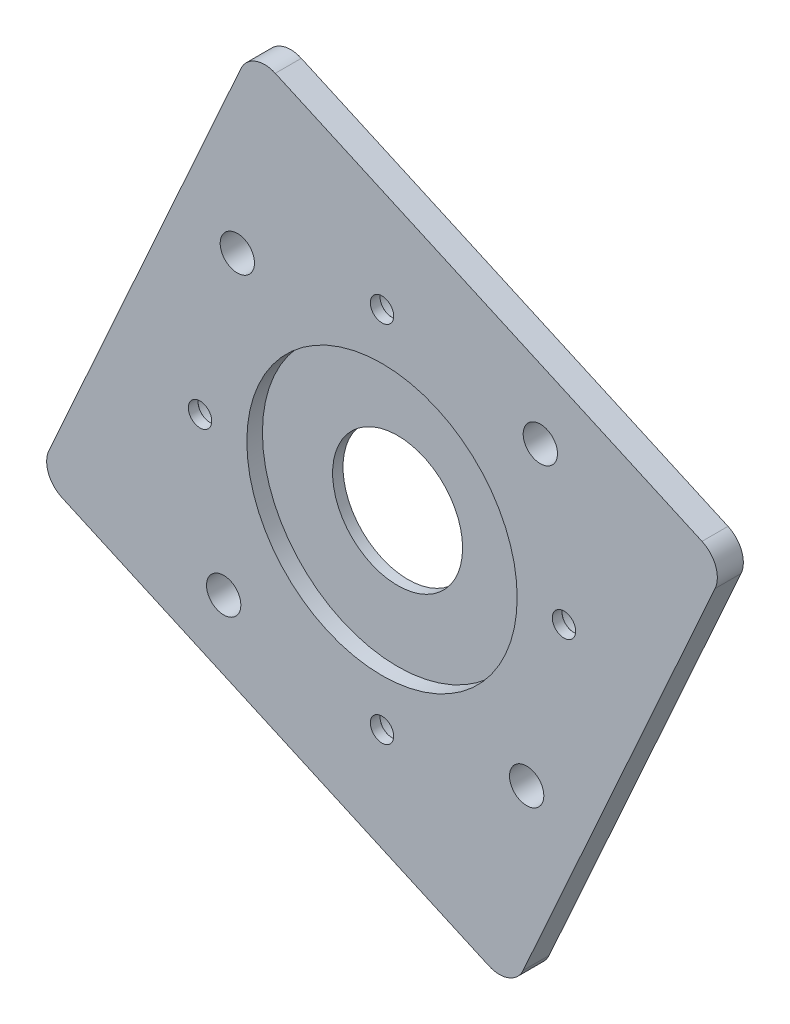
SolidWorks part; units mm, degrees
ref_plane "Plan de face" through (0, 0, 0) normal (0, 0, 1) x (1, 0, 0)
ref_plane "Plan de dessus" through (0, 0, 0) normal (0, 1, 0) x (1, 0, 0)
ref_plane "Plan de droite" through (0, 0, 0) normal (1, 0, 0) x (0, 0, -1)
sketch "Esquisse1" plane through (0, 0, 0) normal (0, 0, 1) x (1, 0, 0)
  circle A0 centre (0, 0) radius 50
  dimension "D1" = 100
extrude "Boss.-Extru.1" add sketch "Esquisse1" along normal blind 5
sketch "Esquisse2" plane through (0, 0, 5) normal (0, 0, 1) x (1, 0, 0)
  circle A1 centre (0, 0) radius 26
  dimension "D2" = 52
extrude "Enlèv. mat.-Extru.1" cut sketch "Esquisse2" against normal blind 3
sketch "Esquisse3" plane through (0, 0, 5) normal (0, 0, 1) x (1, 0, 0)
  circle A0 centre (0, 0) radius 12.5
  dimension "D1" = 25
extrude "Enlèv. mat.-Extru.2" cut sketch "Esquisse3" against normal through all
sketch "Esquisse4" plane through (0, 0, 0) normal (0, 0, -1) x (-1, 0, 0)
  circle A0 centre (0, 0) radius 35 construction
  dimension "D1" = 70
hole_wizard "Chambrage pour vis à tête ronde bombée M41" positions "Esquisse6" profile "Esquisse5" counterbore size "M4" standard "Ansi Metric" end condition through all
sketch "Esquisse6" plane through (0, 0, 0) normal (0, 0, -1) x (-1, 0, 0)
  circle A0 centre (0, 0) radius 35 construction
  point P0 (0, 35)
  point P4 (35, 0)
  point P6 (0, -35)
  point P8 (-35, 0)
sketch "Esquisse5" plane through (0, 35, 0) normal (1, 0, 0) x (0, 1, 0)
  line L0 (0, 0) -> (0, 5)
  line L1 (0, 5) -> (2.25, 5)
  line L2 (2.25, 3.125) -> (2.25, 5)
  line L3 (2.25, 3.125) -> (2.275, 3.1)
  line L4 (2.275, 3.1) -> (4.5, 3.1)
  line L5 (4.5, 3.1) -> (4.5, 0)
  line L7 (0, 0) -> (4.5, 0)
  line L9 (-2.25, 3.125) -> (-2.275, 3.1) construction
  line L11 (0, -6.35) -> (0, 107.95) construction
  dimension "Diamètre du perçage jusqu'au prochain" = 4.5
  dimension "Profondeur du perçage jusqu'au prochain" = 5
  dimension "Diamètre du chambrage" = 9
  dimension "Profondeur du chambrage" = 3.1
  dimension "Diamètre du fraisage milieu" = 4.55
  dimension "Angle du fraisage milieu" = 90
hole_wizard "Dégagement M62" positions "Esquisse10" profile "Esquisse9" hole size "M6" standard "JIS" end condition through all
sketch "Esquisse10" plane through (0, 0, 5) normal (0, 0, 1) x (1, 0, 0)
  point P0 (30.4527, 27.8244)
  point P2 (-27.8244, 30.4527)
  point P4 (-30.4527, -27.8244)
  point P6 (27.8244, -30.4527)
sketch "Esquisse9" plane through (30.4527, 27.8244, 5) normal (1, 0, 0) x (0, -1, 0)
  line L0 (0, 0) -> (0, 5)
  line L1 (0, 5) -> (3.3, 5)
  line L2 (3.3, 5) -> (3.3, 0)
  line L5 (3.3, 0) -> (0, 0)
  line L11 (0, -6.35) -> (0, 107.95) construction
  dimension "Diamètre du perçage jusqu'au prochain" = 6.6
  dimension "Profondeur du perçage jusqu'au prochain" = 5
sketch "Esquisse12" plane through (0, 0, 0) normal (0, 0, -1) x (-1, 0, 0)
  line L12 (-64.0599, 20.5263) -> (-27.1374, -61.5513)
  line L13 (20.5263, 64.0599) -> (-61.5513, 27.1374)
  line L14 (64.0599, -20.5263) -> (27.1374, 61.5513)
  line L15 (-20.5263, -64.0599) -> (61.5513, -27.1374)
  arc A12 (-61.5513, 27.1374) -> (-64.0599, 20.5263) centre (-59.5, 22.5776) ccw
  arc A13 (27.1374, 61.5513) -> (20.5263, 64.0599) centre (22.5776, 59.5) ccw
  arc A14 (61.5513, -27.1374) -> (64.0599, -20.5263) centre (59.5, -22.5776) ccw
  arc A15 (-27.1374, -61.5513) -> (-20.5263, -64.0599) centre (-22.5776, -59.5) ccw
extrude "Boss.-Extru.3" add sketch "Esquisse12" against normal blind 5
